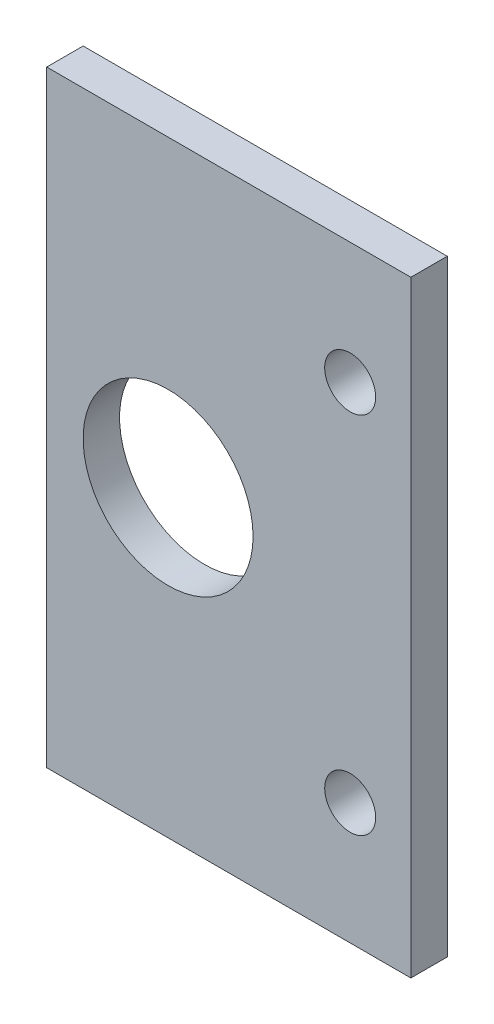
SolidWorks part; units mm, degrees
ref_plane "前视基准面" through (0, 0, 0) normal (0, 0, 1) x (1, 0, 0)
ref_plane "上视基准面" through (0, 0, 0) normal (0, 1, 0) x (1, 0, 0)
ref_plane "右视基准面" through (0, 0, 0) normal (1, 0, 0) x (0, 0, -1)
other "Configuration Table"
sketch "草图1" plane through (0, 0, 0) normal (0, 0, 1) x (1, 0, 0)
  line L1 (0, 0) -> (30, 0)
  line L2 (0, 0) -> (0, -50)
  line L3 (0, -50) -> (30, -50)
  line L4 (30, 0) -> (30, -50)
  dimension "D1" = 30
  dimension "D2" = 50
extrude "凸台-拉伸1" add sketch "草图1" along normal blind 3
sketch "草图2" plane through (0, 0, 3) normal (0, 0, 1) x (1, 0, 0)
  line L0 (0, 0) -> (0, -50) construction
  line L1 (30, 0) -> (0, 0) construction
  line L2 (30, -25) -> (0, -25) construction
  line L3 (30, -50) -> (30, 0) construction
  circle A0 centre (10, -25) radius 7
  circle A1 centre (25, -10) radius 2.1
  circle A2 centre (25, -40) radius 2.1
  point P14 (26.8899, -7.5505)
  dimension "D1" = 14
  dimension "D4" = 4.2
  dimension "D2" = 10
  dimension "D3" = 25
  dimension "D5" = 15
  dimension "D6" = 5
extrude "切除-拉伸1" cut sketch "草图2" against normal through all
